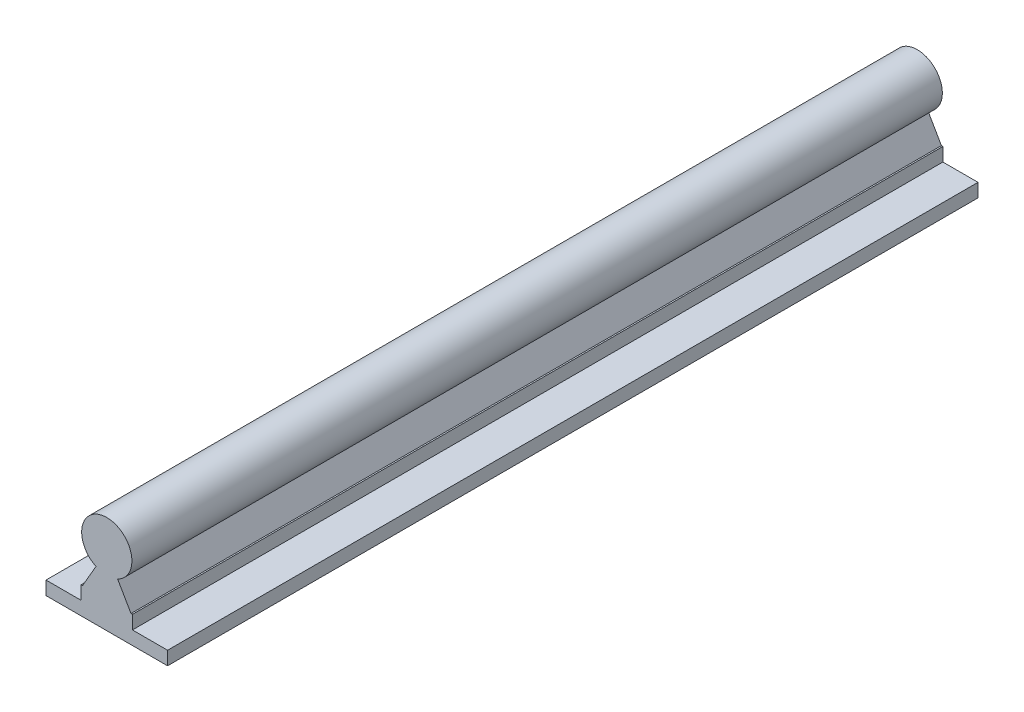
SolidWorks part; units mm, degrees
ref_plane "Front Plane" through (0, 0, 0) normal (0, 0, 1) x (1, 0, 0)
ref_plane "Top Plane" through (0, 0, 0) normal (0, 1, 0) x (1, 0, 0)
ref_plane "Right Plane" through (0, 0, 0) normal (1, 0, 0) x (0, 0, -1)
ref_plane "Plane1"
sketch "Sketch1" plane through (0, 0, 0) normal (0, 0, 1) x (1, 0, 0)
  line L0 (-22.5, 0) -> (22.5, 0)
  line L1 (22.5, 0) -> (22.5, 5)
  line L2 (22.5, 5) -> (9.5, 5)
  line L3 (9.5, 5) -> (9.5, 10)
  line L4 (9.5, 10) -> (8.9676, 10)
  line L5 (8.9676, 10) -> (4, 18.6042)
  line L6 (-4, 18.6042) -> (-8.9676, 10)
  line L7 (-8.9676, 10) -> (-9.5, 10)
  line L8 (-9.5, 10) -> (-9.5, 5)
  line L9 (-9.5, 5) -> (-22.5, 5)
  line L10 (-22.5, 5) -> (-22.5, 0)
  arc A0 (4, 18.6042) -> (-4, 18.6042) centre (0, 27) ccw
  dimension "D8" = 18.6
  dimension "D1" = 45
  dimension "D2" = 5
  dimension "D3" = 5
  dimension "D4" = 19
  dimension "D5" = 13
  dimension "D6" = 10
  dimension "D7" = 5
  dimension "D9" = 8
  dimension "D10" = 270
extrude "Extrusion1" add sketch "Sketch1" along normal blind 300
